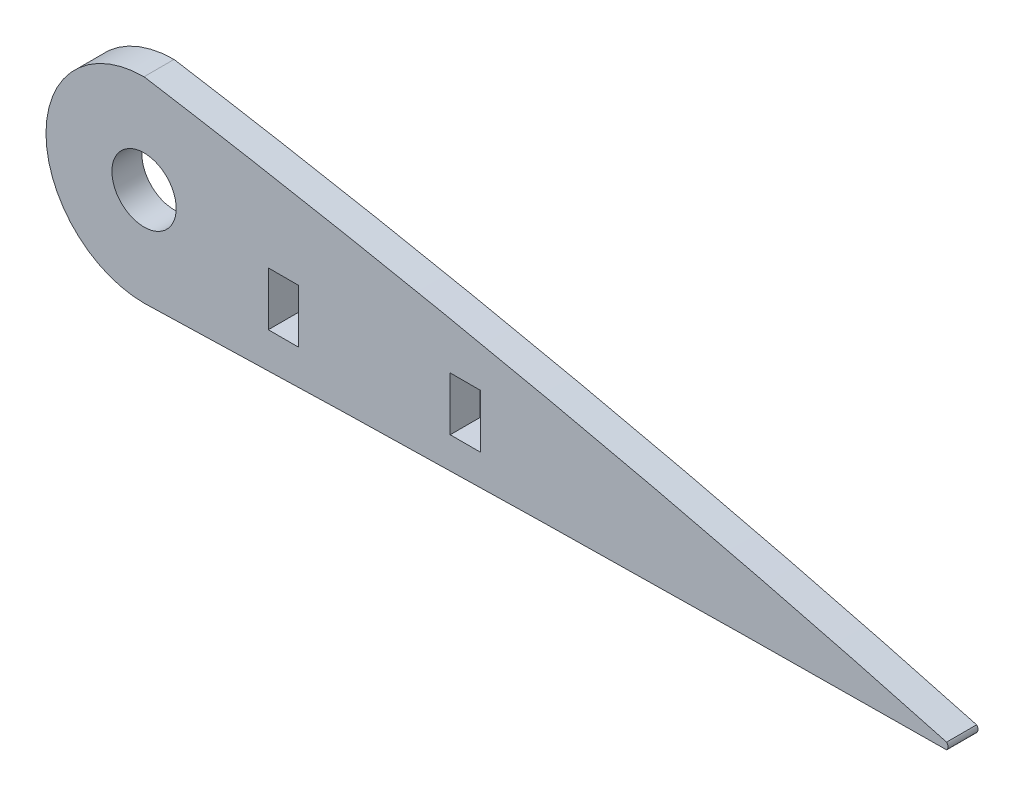
SolidWorks part; units mm, degrees
material "Фанера"
ref_plane "Front Plane" through (0, 0, 0) normal (0, 0, 1) x (1, 0, 0)
ref_plane "Top Plane" through (0, 0, 0) normal (0, 1, 0) x (1, 0, 0)
ref_plane "Right Plane" through (0, 0, 0) normal (1, 0, 0) x (0, 0, -1)
curve "Кривая5"
  spline degree 3 poles (0.048, 0.6214, 0) (0.0227, 0.3735, 0) (-0.0278, -0.1225, 0) (0.078, -0.8844, 0) (0.3497, -1.6388, 0) (0.8143, -2.3651, 0) (1.4635, -3.0393, 0) (2.291, -3.661, 0) (3.3059, -4.2358, 0) (4.5353, -4.7737, 0) (6.0297, -5.2822, 0) (7.869, -5.7653, 0) (10.1688, -6.2217, 0) (13.0754, -6.6396, 0) (16.7281, -6.993, 0) (21.19, -7.2473, 0) (26.4, -7.3766, 0) (32.1974, -7.3763, 0) (38.3978, -7.2614, 0) (44.8576, -7.0566, 0) (51.4865, -6.7865, 0) (58.231, -6.4723, 0) (65.0521, -6.1329, 0) (71.9108, -5.784, 0) (78.7714, -5.4397, 0) (85.6105, -5.111, 0) (92.4321, -4.805, 0) (99.255, -4.532, 0) (106.0974, -4.2783, 0) (112.9692, -4.0031, 0) (119.8644, -3.7232, 0) (126.7739, -3.4401, 0) (133.6816, -3.1587, 0) (140.5819, -2.8824, 0) (147.472, -2.6139, 0) (154.3526, -2.3556, 0) (161.225, -2.1094, 0) (168.0909, -1.8766, 0) (174.9516, -1.6586, 0) (181.8086, -1.4564, 0) (188.6632, -1.2704, 0) (195.5166, -1.1011, 0) (202.3695, -0.9486, 0) (209.2212, -0.8129, 0) (216.0668, -0.6936, 0) (222.8864, -0.5903, 0) (229.6176, -0.5029, 0) (236.0874, -0.4315, 0) (241.9808, -0.3765, 0) (246.559, -0.3395, 0) (249.1205, -0.3213, 0) (250, -0.315, 0) knots 0 0 0 0 0.002941 0.005884 0.009016 0.012365 0.016008 0.020037 0.024574 0.029784 0.035897 0.04324 0.052276 0.063635 0.077983 0.095698 0.11652 0.139661 0.164312 0.189919 0.216157 0.242838 0.269834 0.296993 0.324123 0.351139 0.378036 0.404946 0.431961 0.459078 0.486347 0.513641 0.540929 0.568176 0.59538 0.622543 0.649673 0.676775 0.703855 0.730919 0.757971 0.785018 0.812062 0.839103 0.866132 0.893099 0.919831 0.94581 0.969681 0.98959 1 1 1 1
curve "Кривая6"
  spline degree 3 poles (250, 0.315, 0) (249.1557, 0.545, 0) (246.7202, 1.2085, 0) (242.3913, 2.3583, 0) (236.8498, 3.7876, 0) (230.7799, 5.298, 0) (224.4559, 6.8129, 0) (218.0305, 8.2916, 0) (211.5624, 9.7197, 0) (205.0724, 11.0924, 0) (198.568, 12.4079, 0) (192.0524, 13.6653, 0) (185.5276, 14.8641, 0) (178.9953, 16.0034, 0) (172.4571, 17.0824, 0) (165.9143, 18.0998, 0) (159.3687, 19.0545, 0) (152.8218, 19.9449, 0) (146.2754, 20.7693, 0) (139.7314, 21.5257, 0) (133.1918, 22.212, 0) (126.6587, 22.8257, 0) (120.1368, 23.364, 0) (113.6286, 23.8247, 0) (107.1527, 24.2002, 0) (100.7411, 24.4984, 0) (94.4118, 24.6866, 0) (88.1559, 24.7401, 0) (81.949, 24.6588, 0) (75.7805, 24.441, 0) (69.6537, 24.0819, 0) (63.5754, 23.578, 0) (57.5552, 22.9249, 0) (51.6058, 22.1191, 0) (45.7444, 21.1566, 0) (39.9959, 20.0354, 0) (34.3979, 18.7563, 0) (29.0104, 17.3276, 0) (23.9258, 15.7719, 0) (19.2707, 14.1343, 0) (15.1791, 12.4833, 0) (11.7405, 10.8956, 0) (8.9594, 9.4296, 0) (6.7609, 8.1086, 0) (5.0337, 6.9246, 0) (3.6717, 5.8542, 0) (2.5921, 4.8713, 0) (1.7382, 3.9526, 0) (1.0699, 3.0809, 0) (0.5716, 2.2416, 0) (0.2158, 1.4308, 0) (0.1023, 0.8832, 0) (0.048, 0.6214, 0) knots 0 0 0 0 0.010162 0.029313 0.052012 0.076619 0.101948 0.127526 0.153184 0.178868 0.204558 0.230246 0.255926 0.281594 0.307246 0.332878 0.358485 0.384061 0.409603 0.435104 0.460559 0.485959 0.511303 0.536552 0.561723 0.586629 0.611085 0.635251 0.659272 0.683164 0.706922 0.730536 0.753983 0.777235 0.800246 0.822951 0.845237 0.866916 0.887662 0.906968 0.924203 0.938879 0.950932 0.960693 0.968647 0.975233 0.980795 0.985584 0.989782 0.993521 0.996902 1 1 1 1
sketch "Эскиз1" plane through (0, 0, 0) normal (0, 0, 1) x (1, 0, 0)
  line L0 (250.1305, 0) -> (250.1305, 54.8427) construction
  line L1 (0, 0) -> (0, 70.5199) construction
  line L2 (0, 0) -> (253.0634, 0) construction
  line L3 (62.5326, 62.6361) -> (62.5326, -41.5636) construction
  line L4 (142.5326, 67.9319) -> (142.5326, -57.0034) construction
  line L5 (175.0913, 63.8571) -> (175.0913, -32.3947) construction
  line L6 (32.5326, -14.3434) -> (32.5326, 29.5903) construction
  line L7 (165.9405, 18.0854) -> (165.9405, -1.9504)
  line L8 (205.0913, 4.4939) -> (186.5381, 4.4939) construction
  line L9 (203.6663, 6.9939) -> (206.5163, 6.9939)
  line L10 (203.6663, 6.9939) -> (203.6663, 1.9939)
  line L11 (203.6663, 1.9939) -> (206.5163, 1.9939)
  line L12 (206.5163, 6.9939) -> (206.5163, 1.9939)
  line L13 (203.6663, 6.9939) -> (206.5163, 1.9939) construction
  line L14 (203.6663, 1.9939) -> (206.5163, 6.9939) construction
  line L16 (186.6913, 1.9939) -> (189.4913, 1.9939)
  line L17 (186.6913, 1.9939) -> (186.6913, 6.9939)
  line L18 (186.6913, 6.9939) -> (189.4913, 6.9939)
  line L19 (189.4913, 1.9939) -> (189.4913, 6.9939)
  line L20 (186.6913, 1.9939) -> (189.4913, 6.9939) construction
  line L21 (186.6913, 6.9939) -> (189.4913, 1.9939) construction
  arc A0 (250, 0.315) -> (250, -0.315) centre (249.685, 0) cw
  circle A1 centre (62.5326, 8.5962) radius 8.1
  circle A2 centre (142.5326, 8.5962) radius 5.1
  circle A3 centre (32.5326, 5.4481) radius 7
  circle A5 centre (102.5326, 8.5962) radius 9.5
  arc A6 (175.0913, -1.657) -> (175.0913, 16.6448) centre (175.0913, 7.4939) cw
  circle A7 centre (175.0913, 7.4939) radius 3
  spline S0 degree 3 poles (-1998.9862, 52.2873) (51.3697, 19.9849) (-1.4299, 9.9734) (0.078, -0.8844) (0.3497, -1.6388) (0.8143, -2.3651) (1.4635, -3.0393) (2.291, -3.661) (3.3059, -4.2358) (4.5353, -4.7737) (6.0297, -5.2822) (7.869, -5.7653) (10.1688, -6.2217) (13.0754, -6.6396) (16.7281, -6.993) (21.19, -7.2473) (26.4, -7.3766) (32.1974, -7.3763) (38.3978, -7.2614) (44.8576, -7.0566) (51.4865, -6.7865) (58.231, -6.4723) (65.0521, -6.1329) (71.9108, -5.784) (78.7714, -5.4397) (85.6105, -5.111) (92.4321, -4.805) (99.255, -4.532) (106.0974, -4.2783) (112.9692, -4.0031) (119.8644, -3.7232) (126.7739, -3.4401) (133.6816, -3.1587) (140.5819, -2.8824) (147.472, -2.6139) (154.3526, -2.3556) (161.225, -2.1094) (168.0909, -1.8766) (174.9516, -1.6586) (181.8086, -1.4564) (188.6632, -1.2704) (195.5166, -1.1011) (202.3695, -0.9486) (211.4992, -0.7677) (220.6031, -0.6199) (229.6176, -0.5029) (236.0874, -0.4315) (241.9808, -0.3765) (412.2827, 0.9993) (580.6451, -8.1221) (733.0822, 1918.4656) knots -0.119467 -0.119467 -0.119467 -0.119467 0.002941 0.005884 0.009016 0.012365 0.016008 0.020037 0.024574 0.029784 0.035897 0.04324 0.052276 0.063635 0.077983 0.095698 0.11652 0.139661 0.164312 0.189919 0.216157 0.242838 0.269834 0.296993 0.324123 0.351139 0.378036 0.404946 0.431961 0.459078 0.486347 0.513641 0.540929 0.568176 0.59538 0.622543 0.649673 0.676775 0.703855 0.730919 0.757971 0.785018 0.812062 0.839103 0.893099 0.919831 0.94581 0.969681 0.98959 2.9616 2.9616 2.9616 2.9616 only from (0.048, 0.6214) to (250, -0.315) construction
  spline S1 degree 3 poles (1021.8633, 1838.7787) (414.3615, -64.7736) (332.0293, -21.4512) (242.3913, 2.3583) (236.8498, 3.7876) (230.7799, 5.298) (224.4559, 6.8129) (218.0305, 8.2916) (211.5624, 9.7197) (205.0724, 11.0924) (198.568, 12.4079) (192.0524, 13.6653) (185.5276, 14.8641) (178.9953, 16.0034) (172.4571, 17.0824) (165.9143, 18.0998) (159.3687, 19.0545) (152.8218, 19.9449) (146.2754, 20.7693) (139.7314, 21.5257) (133.1918, 22.212) (126.6587, 22.8257) (120.1368, 23.364) (113.6286, 23.8247) (107.1527, 24.2002) (100.7411, 24.4984) (94.4118, 24.6866) (88.1559, 24.7401) (81.949, 24.6588) (75.7805, 24.441) (69.6537, 24.0819) (63.5754, 23.578) (57.5552, 22.9249) (51.6058, 22.1191) (45.7444, 21.1566) (39.9959, 20.0354) (34.3979, 18.7563) (29.0104, 17.3276) (23.9258, 15.7719) (19.2707, 14.1343) (15.1791, 12.4833) (11.7405, 10.8956) (8.9594, 9.4296) (6.7609, 8.1086) (5.0337, 6.9246) (3.6717, 5.8542) (2.5921, 4.8713) (1.7382, 3.9526) (1.0699, 3.0809) (0.5716, 2.2416) (-4.3308, -8.9285) (41.0506, -34.7699) (-1925.2597, 540.0689) knots -1.025 -1.025 -1.025 -1.025 0.010162 0.029313 0.052012 0.076619 0.101948 0.127526 0.153184 0.178868 0.204558 0.230246 0.255926 0.281594 0.307246 0.332878 0.358485 0.384061 0.409603 0.435104 0.460559 0.485959 0.511303 0.536552 0.561723 0.586629 0.611085 0.635251 0.659272 0.683164 0.706922 0.730536 0.753983 0.777235 0.800246 0.822951 0.845237 0.866916 0.887662 0.906968 0.924203 0.938879 0.950932 0.960693 0.968647 0.975233 0.980795 0.985584 0.989782 0.993521 0.996902 1.130551 1.130551 1.130551 1.130551 only from (250, 0.315) to (0.048, 0.6214) construction
  spline S2 degree 3 poles (0.048, 0.6214) (0.0227, 0.3735) (-0.0278, -0.1225) (0.078, -0.8844) (0.3497, -1.6388) (0.8143, -2.3651) (1.4635, -3.0393) (2.291, -3.661) (3.3059, -4.2358) (4.5353, -4.7737) (6.0297, -5.2822) (7.869, -5.7653) (10.1688, -6.2217) (13.0754, -6.6396) (16.7281, -6.993) (21.19, -7.2473) (26.4, -7.3766) (32.1974, -7.3763) (38.3978, -7.2614) (44.8576, -7.0566) (51.4865, -6.7865) (58.231, -6.4723) (65.0521, -6.1329) (71.9108, -5.784) (78.7714, -5.4397) (85.6105, -5.111) (92.4321, -4.805) (99.255, -4.532) (106.0974, -4.2783) (112.9692, -4.0031) (119.8644, -3.7232) (126.7739, -3.4401) (133.6816, -3.1587) (140.5819, -2.8824) (147.472, -2.6139) (154.3526, -2.3556) (161.225, -2.1094) (168.0909, -1.8766) (174.9516, -1.6586) (181.8086, -1.4564) (188.6632, -1.2704) (195.5166, -1.1011) (202.3695, -0.9486) (211.4992, -0.7677) (220.6031, -0.6199) (229.6176, -0.5029) (236.0874, -0.4315) (241.9808, -0.3765) (246.559, -0.3395) (249.1205, -0.3213) (250, -0.315) knots 0 0 0 0 0.002941 0.005884 0.009016 0.012365 0.016008 0.020037 0.024574 0.029784 0.035897 0.04324 0.052276 0.063635 0.077983 0.095698 0.11652 0.139661 0.164312 0.189919 0.216157 0.242838 0.269834 0.296993 0.324123 0.351139 0.378036 0.404946 0.431961 0.459078 0.486347 0.513641 0.540929 0.568176 0.59538 0.622543 0.649673 0.676775 0.703855 0.730919 0.757971 0.785018 0.812062 0.839103 0.893099 0.919831 0.94581 0.969681 0.98959 1 1 1 1
  spline S3 degree 3 poles (250, 0.315) (249.1557, 0.545) (246.7202, 1.2085) (242.3913, 2.3583) (236.8498, 3.7876) (230.7799, 5.298) (224.4559, 6.8129) (218.0305, 8.2916) (211.5624, 9.7197) (205.0724, 11.0924) (198.568, 12.4079) (192.0524, 13.6653) (185.5276, 14.8641) (178.9953, 16.0034) (172.4571, 17.0824) (165.9143, 18.0998) (159.3687, 19.0545) (152.8218, 19.9449) (146.2754, 20.7693) (139.7314, 21.5257) (133.1918, 22.212) (126.6587, 22.8257) (120.1368, 23.364) (113.6286, 23.8247) (107.1527, 24.2002) (100.7411, 24.4984) (94.4118, 24.6866) (88.1559, 24.7401) (81.949, 24.6588) (75.7805, 24.441) (69.6537, 24.0819) (63.5754, 23.578) (57.5552, 22.9249) (51.6058, 22.1191) (45.7444, 21.1566) (39.9959, 20.0354) (34.3979, 18.7563) (29.0104, 17.3276) (23.9258, 15.7719) (19.2707, 14.1343) (15.1791, 12.4833) (11.7405, 10.8956) (8.9594, 9.4296) (6.7609, 8.1086) (5.0337, 6.9246) (3.6717, 5.8542) (2.5921, 4.8713) (1.7382, 3.9526) (1.0699, 3.0809) (0.5716, 2.2416) (0.2158, 1.4308) (0.1023, 0.8832) (0.048, 0.6214) knots 0 0 0 0 0.010162 0.029313 0.052012 0.076619 0.101948 0.127526 0.153184 0.178868 0.204558 0.230246 0.255926 0.281594 0.307246 0.332878 0.358485 0.384061 0.409603 0.435104 0.460559 0.485959 0.511303 0.536552 0.561723 0.586629 0.611085 0.635251 0.659272 0.683164 0.706922 0.730536 0.753983 0.777235 0.800246 0.822951 0.845237 0.866916 0.887662 0.906968 0.924203 0.938879 0.950932 0.960693 0.968647 0.975233 0.980795 0.985584 0.989782 0.993521 0.996902 1 1 1 1
  point P22 (62.5326, 23.4501)
  point P23 (62.5326, -6.2577)
  point P26 (32.5326, 18.2506)
  point P27 (32.5326, -7.3543)
  point P30 (175.0913, 16.6448)
  point P31 (175.0913, -1.657)
  point P37 (205.0913, 4.4939)
  point P45 (188.0913, 4.4939)
  point P50 (188.0913, 1.9939)
  dimension "D3" = 16.2
  dimension "D8" = 14
  dimension "D10" = 10.2
  dimension "D9" = 19
  dimension "D15" = 9.1509
  dimension "D16" = 6
  dimension "D1" = 250.1305
  dimension "D2" = 62.5326
  dimension "D4" = 80
  dimension "D5" = 75.0391
  dimension "D6" = 29.7079
  dimension "D7" = 14.8539
  dimension "D11" = 40
  dimension "D12" = 30
  dimension "D13" = 25.6049
  dimension "D14" = 12.8025
  dimension "D17" = 2.85
  dimension "D18" = 5
  dimension "D19" = 30
  dimension "D20" = 3
  dimension "D21" = 5
  dimension "D22" = 2.8
  dimension "D23" = 17
extrude "Бобышка-Вытянуть1" add sketch "Эскиз1" along normal mid plane 2.8 contours A0 S3 A6 S2 A7
equation "\"D2@Эскиз1\"=\"D1@Эскиз1\"/4"
equation "\"D7@Эскиз1\"=\"D6@Эскиз1\"/2"
equation "\"D5@Эскиз1\"=\"D1@Эскиз1\"*0.3"
equation "\"D14@Эскиз1\"=\"D13@Эскиз1\"/2"
equation "\"t\"= 2.85"
